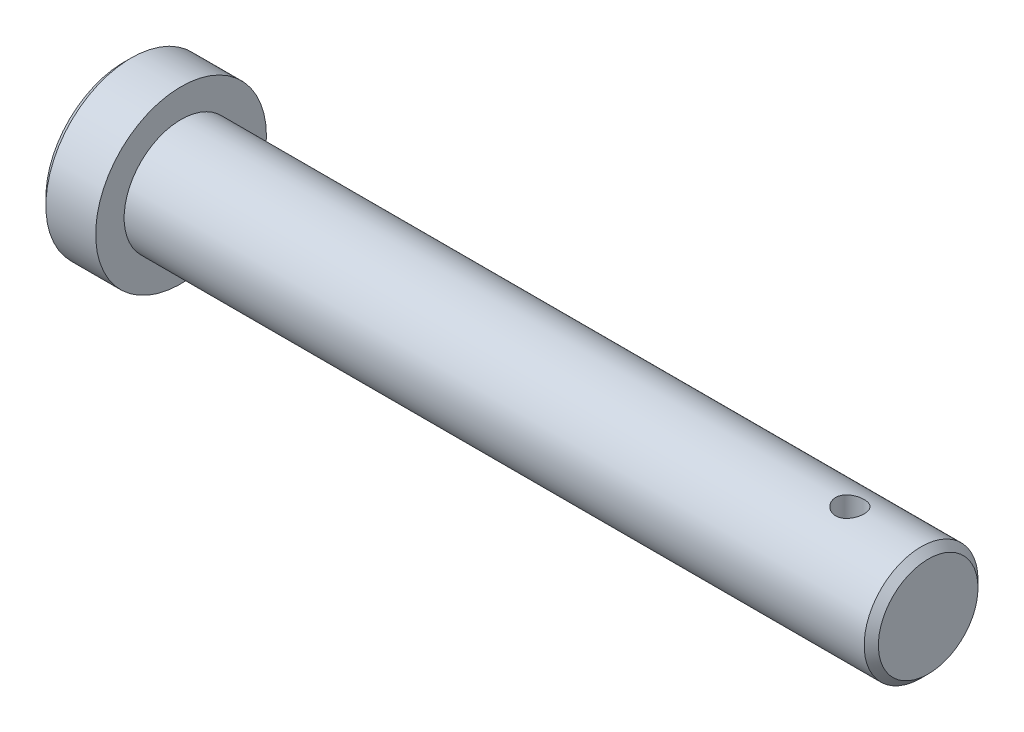
SolidWorks part; units mm, degrees
ref_plane "Front Plane" through (0, 0, 0) normal (0, 0, 1) x (1, 0, 0)
ref_plane "Top Plane" through (0, 0, 0) normal (0, 1, 0) x (1, 0, 0)
ref_plane "Right Plane" through (0, 0, 0) normal (1, 0, 0) x (0, 0, -1)
sketch "Sketch2" plane through (0, 0, 0) normal (1, 0, 0) x (0, 0, -1)
  circle A0 centre (0, 0) radius 12
  dimension "D1" = 24
extrude "Boss-Extrude1" add sketch "Sketch2" along normal blind 8
chamfer "Chamfer1" distance 1 angle 45 1 edges at (0, 0, -12)
sketch "Sketch3" plane through (8, 0, 0) normal (1, 0, 0) x (0, 0, -1)
  circle A0 centre (0, 0) radius 8
  dimension "D1" = 16
extrude "Boss-Extrude2" add sketch "Sketch3" along normal blind 105
chamfer "Chamfer2" distance 1 angle 45 1 edges at (113, 0, -8)
sketch "Sketch4" plane through (0, 0, 0) normal (0, 1, 0) x (1, 0, 0)
  line L0 (8, -12) -> (8, 12) construction
  circle A0 centre (102, 0) radius 2
  dimension "D1" = 4
  dimension "D2" = 94
extrude "Cut-Extrude1" cut sketch "Sketch4" against normal mid plane 105
